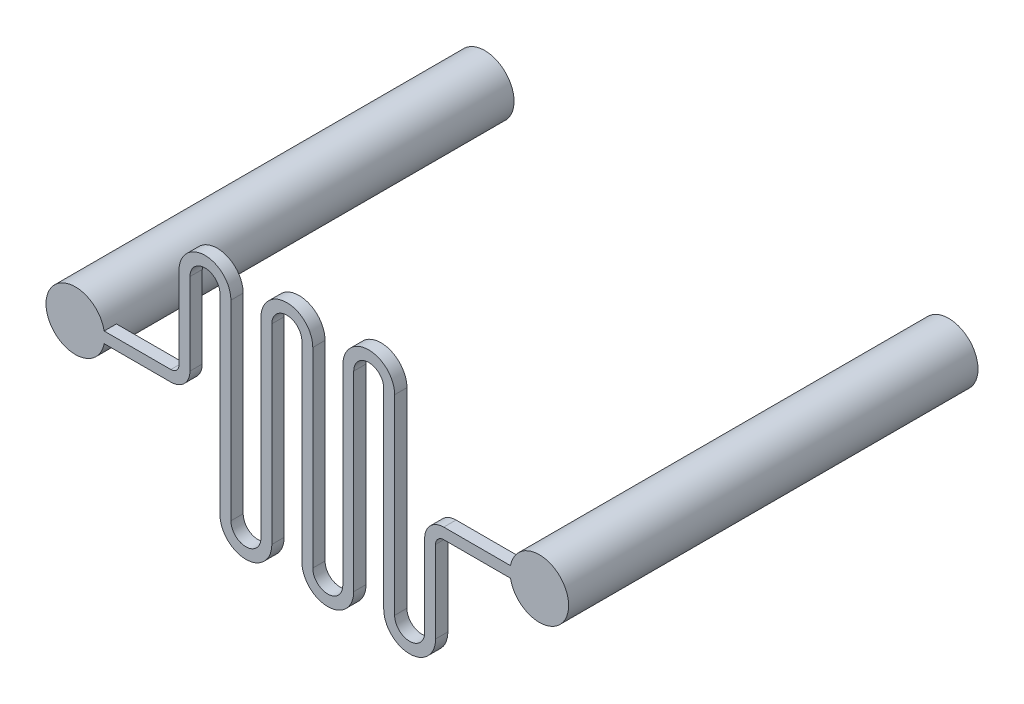
SolidWorks part; units mm, degrees
ref_plane "Front Plane" through (0, 0, 0) normal (0, 0, 1) x (1, 0, 0)
ref_plane "Top Plane" through (0, 0, 0) normal (0, 1, 0) x (1, 0, 0)
ref_plane "Right Plane" through (0, 0, 0) normal (1, 0, 0) x (0, 0, -1)
sketch "Sketch2" plane through (0, 0, 0) normal (0, 0, 1) x (1, 0, 0)
  line L3 (-20.5, -0.4) -> (-13.5, -0.4)
  line L6 (-12.1, 1) -> (-12.1, 7)
  line L9 (-9.9, 7) -> (-9.9, 0)
  line L12 (-9.9, 0) -> (-9.9, -7)
  line L15 (-6.1, -7) -> (-6.1, 0)
  line L18 (-6.1, 0) -> (-6.1, 7)
  line L21 (-3.9, 7) -> (-3.9, 0)
  line L22 (-3.9, 0) -> (-3.9, -7)
  line L23 (-0.1, -7) -> (-0.1, 0)
  line L24 (-0.1, 0) -> (-0.1, 7)
  line L25 (2.1, 7) -> (2.1, 0)
  line L26 (2.1, 0) -> (2.1, -7)
  line L27 (5.9, -7) -> (5.9, -1)
  line L28 (6.5, -0.4) -> (13.5, -0.4)
  line L29 (-20.5, 0.4) -> (-13.5, 0.4)
  line L30 (-12.9, 1) -> (-12.9, 7)
  line L31 (-9.1, 7) -> (-9.1, 0)
  line L32 (-9.1, 0) -> (-9.1, -7)
  line L33 (-6.9, -7) -> (-6.9, 0)
  line L34 (-6.9, 0) -> (-6.9, 7)
  line L35 (-3.1, 7) -> (-3.1, 0)
  line L36 (-3.1, 0) -> (-3.1, -7)
  line L37 (-0.9, -7) -> (-0.9, 0)
  line L38 (-0.9, 0) -> (-0.9, 7)
  line L39 (2.9, 7) -> (2.9, 0)
  line L40 (2.9, 0) -> (2.9, -7)
  line L41 (5.1, -7) -> (5.1, -1)
  line L42 (6.5, 0.4) -> (13.5, 0.4)
  arc A0 (-20.5, 0.4) -> (-20.5, -0.4) centre (-20.5, 0) ccw
  arc A1 (13.5, -0.4) -> (13.5, 0.4) centre (13.5, 0) ccw
  arc A8 (-12.1, 1) -> (-13.5, -0.4) centre (-13.5, 1) cw
  arc A9 (-12.1, 7) -> (-9.9, 7) centre (-11, 7) cw
  arc A10 (-9.9, -7) -> (-6.1, -7) centre (-8, -7) ccw
  arc A11 (-6.1, 7) -> (-3.9, 7) centre (-5, 7) cw
  arc A12 (-3.9, -7) -> (-0.1, -7) centre (-2, -7) ccw
  arc A13 (-0.1, 7) -> (2.1, 7) centre (1, 7) cw
  arc A14 (2.1, -7) -> (5.9, -7) centre (4, -7) ccw
  arc A15 (5.9, -1) -> (6.5, -0.4) centre (6.5, -1) cw
  arc A16 (-12.9, 1) -> (-13.5, 0.4) centre (-13.5, 1) cw
  arc A17 (-12.9, 7) -> (-9.1, 7) centre (-11, 7) cw
  arc A18 (-9.1, -7) -> (-6.9, -7) centre (-8, -7) ccw
  arc A19 (-6.9, 7) -> (-3.1, 7) centre (-5, 7) cw
  arc A20 (-3.1, -7) -> (-0.9, -7) centre (-2, -7) ccw
  arc A21 (-0.9, 7) -> (2.9, 7) centre (1, 7) cw
  arc A22 (2.9, -7) -> (5.1, -7) centre (4, -7) ccw
  arc A23 (5.1, -1) -> (6.5, 0.4) centre (6.5, -1) cw
  point P4 (0, 0)
  point P32 (5.5, 0)
  point P35 (-12.5, 0)
extrude "Boss-Extrude1" add sketch "Sketch2" along normal blind 0.9
ref_plane "Plane1" through (0, 0, 0) normal (0, 1, 0) x (1, 0, 0)
sketch "Sketch3" plane through (0, 0, 0) normal (0, 1, 0) x (1, 0, 0)
  line L0 (-20.5, -0.9) -> (-22.65, -0.9)
  line L2 (-20.5, -0.9) -> (-20.5, 29.1)
  line L3 (-20.5, 29.1) -> (-22.65, 29.1)
  line L7 (-22.65, 29.1) -> (-22.65, -0.9)
  dimension "D1" = 2.15
  dimension "D3" = 30
ref_plane "Plane2" through (0, 0, 0) normal (0, 1, 0) x (1, 0, 0)
sketch "Sketch4" plane through (0, 0, 0) normal (0, 1, 0) x (1, 0, 0)
  line L0 (13.5, -0.9) -> (15.65, -0.9)
  line L1 (15.65, 29.1) -> (15.65, -0.9)
  line L2 (13.5, -0.9) -> (13.5, 29.1)
  line L3 (13.5, 29.1) -> (15.65, 29.1)
  dimension "D1" = 30
  dimension "D2" = 2.15
  dimension "D4" = 2.15
revolve "Revolve1" add sketch "Sketch3" angle 360 about L2
revolve "Revolve2" add sketch "Sketch4" angle 360 about L2
sketch "Sketch5" plane through (0, 0, -29.1) normal (0, 0, -1) x (-1, 0, 0)
  circle A0 centre (-13.5, 0) radius 1.75
  circle A1 centre (20.5, 0) radius 1.75
  dimension "D1" = 3.5
  dimension "D2" = 3.5
extrude "Cut-Extrude1" cut sketch "Sketch5" against normal blind 29
